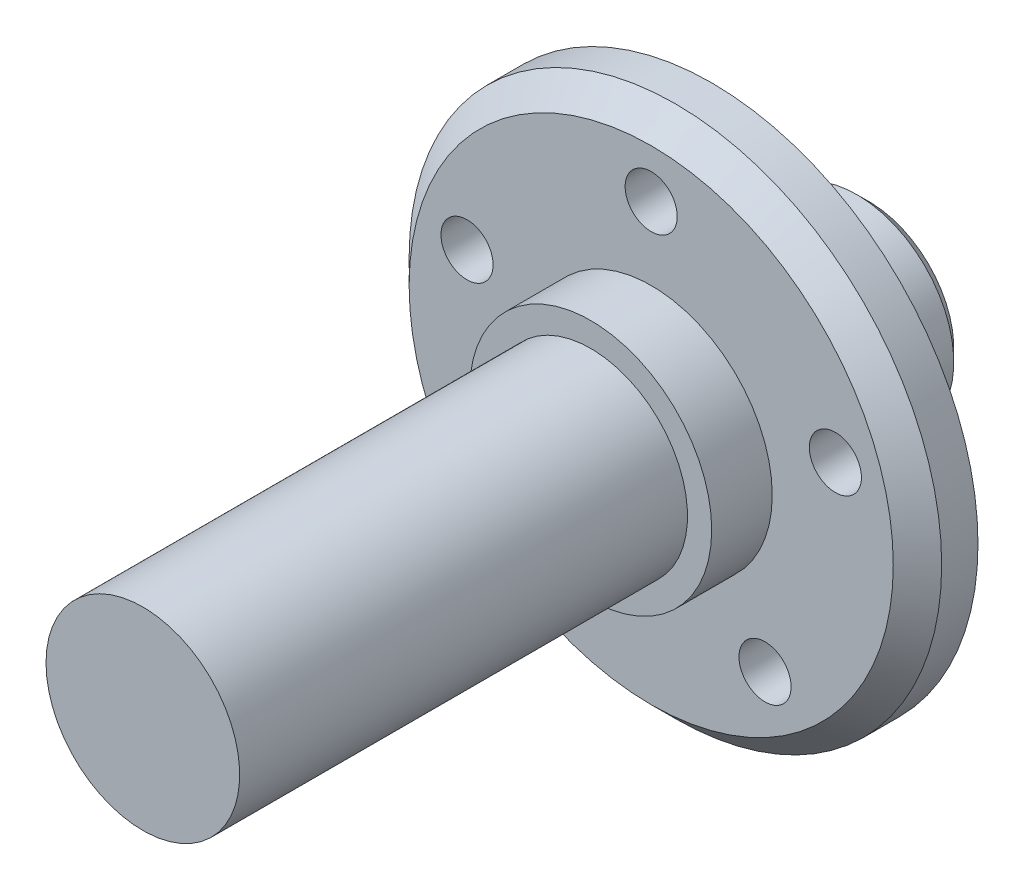
SolidWorks part; units mm, degrees
ref_plane "Front Plane" through (0, 0, 0) normal (0, 0, 1) x (1, 0, 0)
ref_plane "Top Plane" through (0, 0, 0) normal (0, 1, 0) x (1, 0, 0)
ref_plane "Right Plane" through (0, 0, 0) normal (1, 0, 0) x (0, 0, -1)
sketch "Sketch3" plane through (0, 0, 0) normal (0, 1, 0) x (1, 0, 0)
  line L0 (0, 0) -> (-8, 0)
  line L1 (-8, 0) -> (-8, 37)
  line L2 (-8, 37) -> (-10, 37)
  line L5 (0, 60) -> (0, 0)
  line L6 (-10, 37) -> (-10, 42)
  line L7 (-10, 42) -> (-22, 42)
  line L8 (-22, 42) -> (-22, 47)
  line L9 (-22, 47) -> (-8, 47)
  line L10 (-8, 47) -> (-8, 60)
  line L11 (-8, 60) -> (0, 60)
  dimension "D1" = 60
  dimension "D3" = 8
  dimension "D2" = 10
  dimension "D5" = 5
  dimension "D6" = 5
  dimension "D4" = 22
  dimension "D7" = 8
  dimension "D8" = 13
revolve "Revolve1" add sketch "Sketch3" angle 360 about L5
chamfer "Chamfer1" distance 2 angle 45 1 edges at (-22, 0, -42)
sketch "Placement Sketch" plane through (0, 0, -42) normal (0, 0, 1) x (1, 0, 0)
  line L0 (0, 0) -> (0, 16) construction
  point P0 (0, 16)
  point P1 (15.2169, 4.9443)
  point P5 (9.4046, -12.9443)
  point P6 (-9.4046, -12.9443)
  point P7 (-15.2169, 4.9443)
  dimension "D1" = 16
  dimension "D2" = 5
hole_wizard "#8 Clearance Hole1" positions "Placement Sketch" profile "Sketch5" hole size "#8" standard "ANSI Inch"
sketch "Sketch5" plane through (0, 16, -42) normal (1, 0, 0) x (0, -1, 0)
  line L0 (0, 0) -> (0, 13.2934)
  line L1 (0, 13.2934) -> (2.1526, 12)
  line L2 (2.1526, 12) -> (2.1526, 0)
  line L5 (2.1526, 0) -> (0, 0)
  line L10 (0, 13.2934) -> (-2.1527, 12) construction
  line L11 (0, -6.35) -> (0, 107.95) construction
  dimension "Hole Dia." = 4.3053
  dimension "Hole Depth" = 12
  dimension "Drill Angle" = 118
chamfer "Chamfer2" distance 1 angle 45 1 edges at (-8, 0, -60)
equation "\"thin_diameter\"= 16"
equation "\"thick_diameter\"= 20"
equation "\"D3@Sketch3\" = \"thin_diameter\" / 2"
equation "\"D2@Sketch3\" = \"thick_diameter\" / 2"
equation "\"flange_diameter\"= 44"
equation "\"flange_thickness\"= 5"
equation "\"D5@Sketch3\"=\"flange_thickness\""
equation "\"D4@Sketch3\"=\"flange_diameter\" / 2"
equation "\"back_diameter\"= 16"
equation "\"D7@Sketch3\"=\"back_diameter\" / 2"
equation "\"turbine_thickness\"= 13"
equation "\"D8@Sketch3\"=\"turbine_thickness\""
